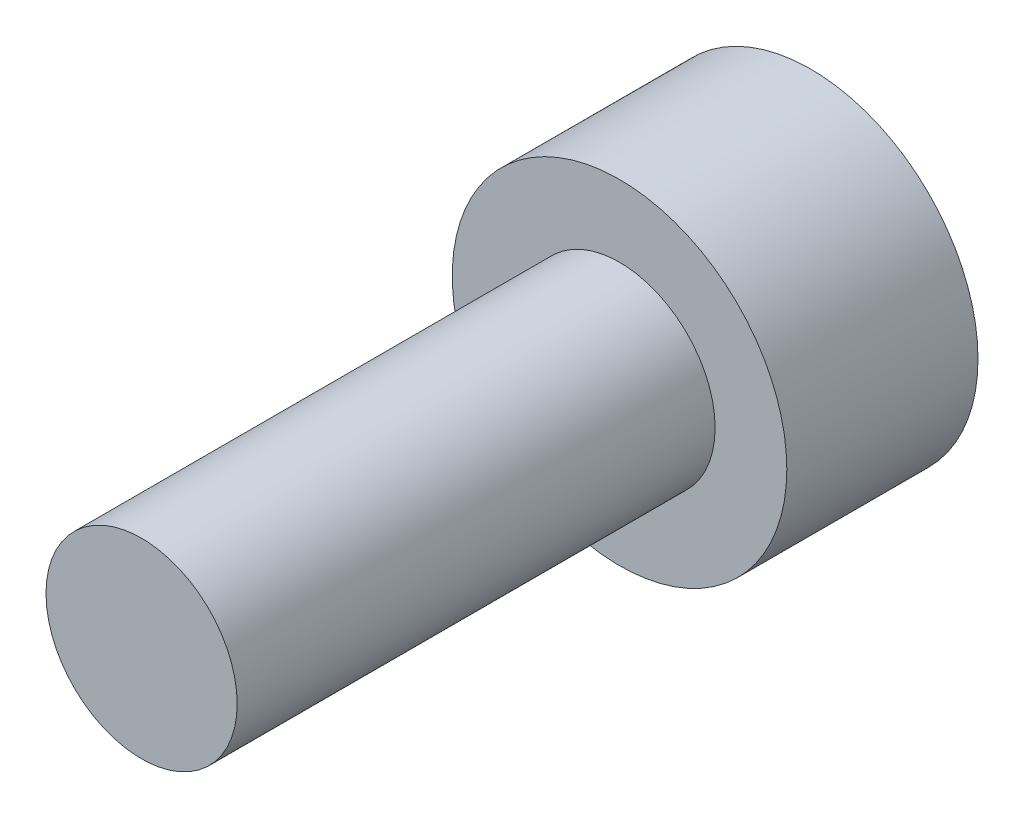
SolidWorks part; units mm, degrees
material "不锈钢 (铁素体)"
ref_plane "前视基准面" through (0, 0, 0) normal (0, 0, 1) x (1, 0, 0)
ref_plane "上视基准面" through (0, 0, 0) normal (0, 1, 0) x (1, 0, 0)
ref_plane "右视基准面" through (0, 0, 0) normal (1, 0, 0) x (0, 0, -1)
other "Configuration Table"
sketch "草图1" plane through (0, 0, 0) normal (0, 0, 1) x (1, 0, 0)
  circle A0 centre (0, 0) radius 3.5
  dimension "D1" = 7
extrude "凸台-拉伸1" add sketch "草图1" along normal blind 4
sketch "草图2" plane through (0, 0, 4) normal (0, 0, 1) x (1, 0, 0)
  circle A0 centre (0, 0) radius 2
  dimension "D1" = 4
extrude "凸台-拉伸2" add sketch "草图2" along normal blind 10
